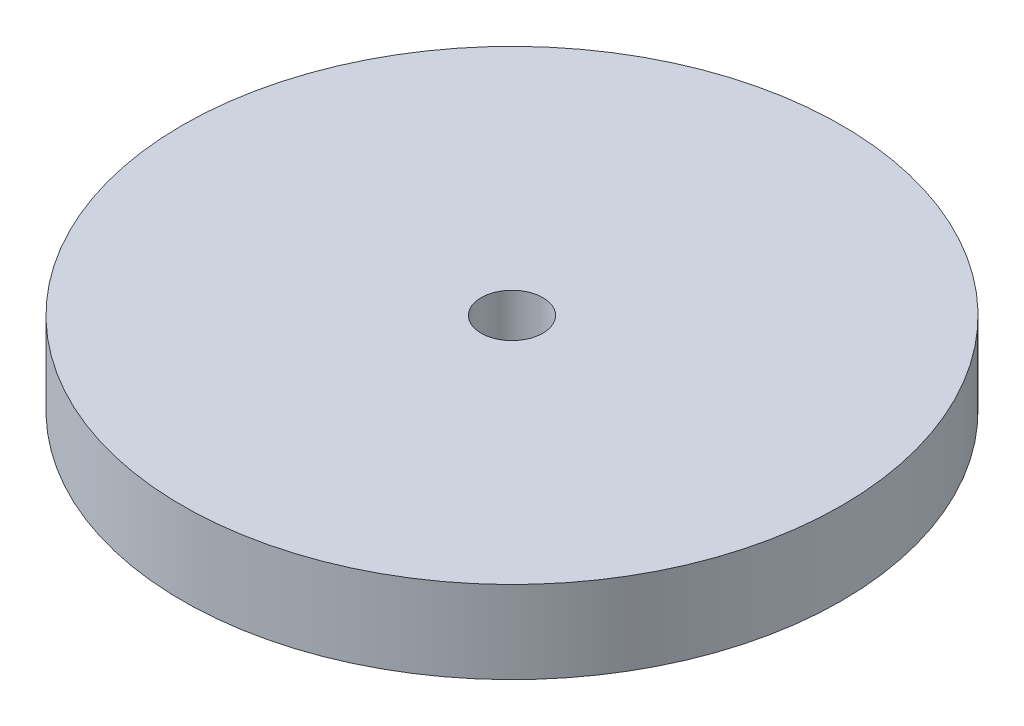
SolidWorks part; units mm, degrees
material "Custom Plastic"
ref_plane "Front Plane" through (0, 0, 0) normal (0, 0, 1) x (1, 0, 0)
ref_plane "Top Plane" through (0, 0, 0) normal (0, 1, 0) x (1, 0, 0)
ref_plane "Right Plane" through (0, 0, 0) normal (1, 0, 0) x (0, 0, -1)
sketch "Sketch3" plane through (0, 0, 0) normal (0, 0, 1) x (1, 0, 0)
  line L1 (-38.1, 4.7625) -> (38.1, 4.7625)
  line L2 (-38.1, 4.7625) -> (-38.1, -4.7625)
  line L3 (-38.1, -4.7625) -> (38.1, -4.7625)
  line L4 (38.1, 4.7625) -> (38.1, -4.7625)
  line L5 (-38.1, 4.7625) -> (38.1, -4.7625) construction
  line L6 (-38.1, -4.7625) -> (38.1, 4.7625) construction
  point P0 (0, 0)
extrude "Boss-Extrude1" add sketch "Sketch3" along normal blind 76.2
sketch "Sketch4" plane through (0, 4.7625, 0) normal (0, 1, 0) x (1, 0, 0)
  line L0 (-38.1, -76.2) -> (-38.1, 0) construction
  line L1 (-38.1, -76.2) -> (-38.1, 0)
  line L2 (38.1, 0) -> (-38.1, 0) construction
  line L3 (38.1, 0) -> (-38.1, 0)
  line L4 (38.1, -76.2) -> (38.1, 0) construction
  line L5 (38.1, -76.2) -> (38.1, 0)
  line L6 (38.1, -76.2) -> (-38.1, -76.2) construction
  line L7 (38.1, -76.2) -> (-38.1, -76.2)
  circle A0 centre (0, -38.1) radius 3.5687
  dimension "D1" = 38.1
  dimension "D2" = 38.1
extrude "Cut-Extrude2" cut sketch "Sketch4" against normal through all
sketch "Sketch5" plane through (0, 4.7625, 0) normal (0, 1, 0) x (1, 0, 0)
  line L2 (-38.1, -38.1) -> (-38.1, 0)
  line L3 (-38.1, 0) -> (0, 0)
  arc A0 (0, 0) -> (-38.1, -38.1) centre (0, -38.1) ccw
extrude "Cut-Extrude4" cut sketch "Sketch5" against normal blind 12.7 contours A0 L2 L3
sketch "Sketch7" plane through (0, 4.7625, 0) normal (0, 1, 0) x (1, 0, 0)
  line L1 (0, 0) -> (38.1, 0)
  line L2 (38.1, 0) -> (38.1, -38.1)
  arc A0 (0, 0) -> (-38.1, -38.1) centre (0, -38.1) ccw construction
  arc A1 (38.1, -38.1) -> (0, 0) centre (0, -38.1) ccw
extrude "Cut-Extrude6" cut sketch "Sketch7" against normal blind 12.7
sketch "Sketch8" plane through (0, 4.7625, 0) normal (0, 1, 0) x (1, 0, 0)
  line L1 (38.1, -76.2) -> (38.1, -38.1) construction
  line L2 (38.1, -76.2) -> (-38.1, -76.2) construction
  line L4 (38.1, -76.2) -> (38.1, -38.1)
  line L5 (38.1, -76.2) -> (0, -76.2)
  arc A0 (38.1, -38.1) -> (-38.1, -38.1) centre (0, -38.1) ccw construction
  arc A1 (0, -76.2) -> (38.1, -38.1) centre (0, -38.1) ccw
extrude "Cut-Extrude9" cut sketch "Sketch8" against normal blind 12.7 contours A1 L4 L5
sketch "Sketch9" plane through (0, 4.7625, 0) normal (0, 1, 0) x (1, 0, 0)
  line L1 (0, -76.2) -> (-38.1, -76.2) construction
  line L2 (-38.1, -76.2) -> (-38.1, -38.1) construction
  line L3 (0, -76.2) -> (-38.1, -76.2)
  line L4 (-38.1, -76.2) -> (-38.1, -38.1)
  arc A1 (0, -76.2) -> (-38.1, -38.1) centre (0, -38.1) ccw construction
  arc A2 (-38.1, -38.1) -> (0, -76.2) centre (0, -38.1) ccw
extrude "Cut-Extrude10" cut sketch "Sketch9" against normal blind 12.7
